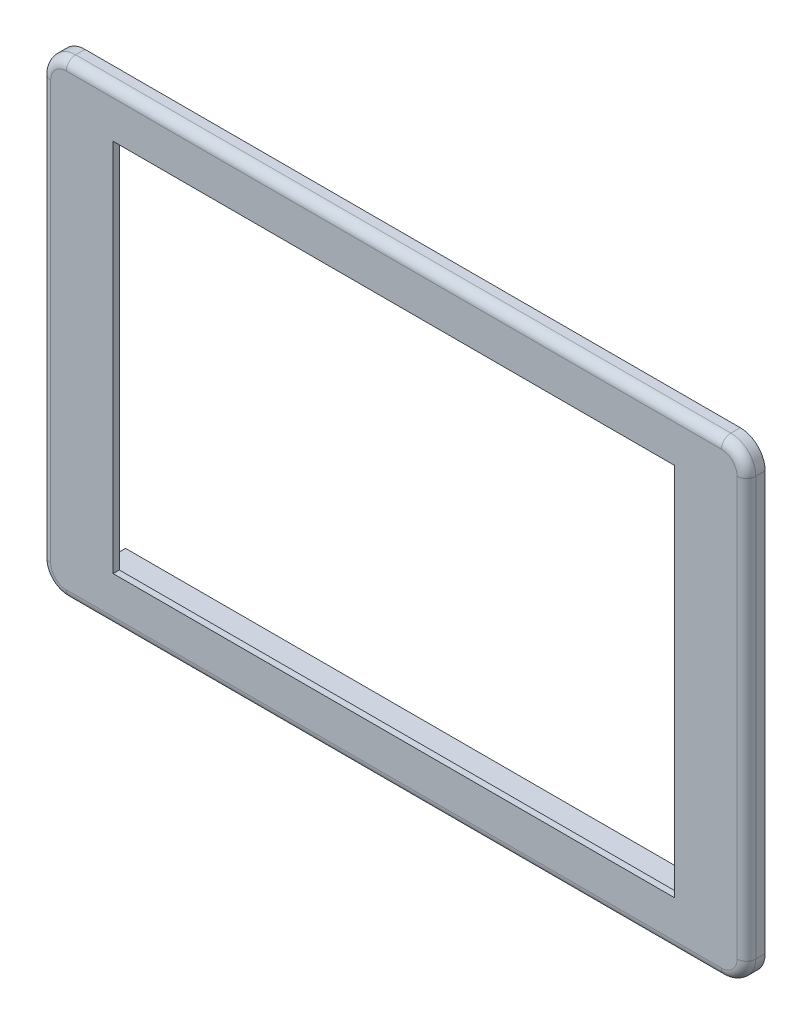
SolidWorks part; units mm, degrees
ref_plane "Front Plane" through (0, 0, 0) normal (0, 0, 1) x (1, 0, 0)
ref_plane "Top Plane" through (0, 0, 0) normal (0, 1, 0) x (1, 0, 0)
ref_plane "Right Plane" through (0, 0, 0) normal (1, 0, 0) x (0, 0, -1)
sketch "Sketch1" plane through (0, 0, 0) normal (0, 0, 1) x (1, 0, 0)
  line L1 (-82.521, 40.8431) -> (30.479, 40.8431)
  line L2 (-82.521, 40.8431) -> (-82.521, -34.1569)
  line L3 (-82.521, -34.1569) -> (30.479, -34.1569)
  line L4 (30.479, 40.8431) -> (30.479, -34.1569)
  line L5 (-75.021, 34.8431) -> (22.979, 34.8431)
  line L6 (-75.021, 34.8431) -> (-75.021, -28.1569)
  line L7 (-75.021, -28.1569) -> (22.979, -28.1569)
  line L8 (22.979, 34.8431) -> (22.979, -28.1569)
  point P8 (-26.021, 34.8431)
  point P9 (-26.021, 40.8431)
  point P10 (-75.021, 3.3431)
  point P11 (-82.521, 3.3431)
  dimension "D1" = 75
  dimension "D2" = 113
  dimension "D3" = 98
  dimension "D4" = 63
  dimension "D5" = 0
extrude "Boss-Extrude1" add sketch "Sketch1" along normal blind 3
fillet "Fillet1" radius 4 4 edges at (-82.521, 40.8431, 1.5) (-82.521, -34.1569, 1.5) (30.479, -34.1569, 1.5) (30.479, 40.8431, 1.5)
sketch "Sketch2" plane through (0, 0, 0) normal (0, 0, -1) x (-1, 0, 0)
  line L1 (-22.979, 34.8431) -> (75.021, 34.8431)
  line L2 (-22.979, 34.8431) -> (-22.979, 37.3431)
  line L3 (-22.979, 37.3431) -> (75.021, 37.3431)
  line L4 (75.021, 34.8431) -> (75.021, 37.3431)
  line L5 (-22.979, -28.1569) -> (75.021, -28.1569)
  line L6 (-22.979, -28.1569) -> (-22.979, -30.6569)
  line L7 (-22.979, -30.6569) -> (75.021, -30.6569)
  line L8 (75.021, -28.1569) -> (75.021, -30.6569)
  dimension "D1" = 2.5
  dimension "D2" = 2.5
extrude "Boss-Extrude2" add sketch "Sketch2" along normal blind 3
fillet "Fillet2" radius 1.5 8 edges at (-81.3494, -32.9853, 3) (-81.3494, 39.6715, 3) (29.3075, 39.6715, 3) (29.3075, -32.9853, 3) (30.479, 3.3431, 3) (-26.021, 40.8431, 3) (-82.521, 3.3431, 3) (-26.021, -34.1569, 3)
sketch "Sketch3" plane through (0, 0, 3) normal (0, 0, 1) x (1, 0, 0)
  line L1 (-75.021, 34.8431) -> (22.979, 34.8431)
  line L2 (-75.021, 34.8431) -> (-75.021, -28.1569)
  line L3 (-75.021, -28.1569) -> (22.979, -28.1569)
  line L4 (22.979, 34.8431) -> (22.979, -28.1569)
  line L5 (-71.021, 33.3431) -> (18.979, 33.3431)
  line L6 (-71.021, 33.3431) -> (-71.021, -26.6569)
  line L7 (-71.021, -26.6569) -> (18.979, -26.6569)
  line L8 (18.979, 33.3431) -> (18.979, -26.6569)
  point P10 (-26.021, 33.3431)
  point P11 (-26.021, 34.8431)
  point P12 (-71.021, 3.3431)
  point P13 (-75.021, 3.3431)
  dimension "D1" = 90
  dimension "D2" = 60
extrude "Boss-Extrude3" add sketch "Sketch3" against normal blind 1
sketch "Sketch4" plane through (-75.021, 0, 0) normal (-1, 0, 0) x (0, 0, 1)
  line L5 (0, 37.3431) -> (-2.5, 34.8431)
  line L6 (-3, 34.8431) -> (0, 34.8431) construction
  line L7 (-2.5, 34.8431) -> (-3, 34.8431)
  line L8 (-3, 34.8431) -> (-3, 37.3431)
  line L9 (-3, 37.3431) -> (0, 37.3431)
extrude "Cut-Extrude1" cut sketch "Sketch4" against normal through all both and the other way through all
